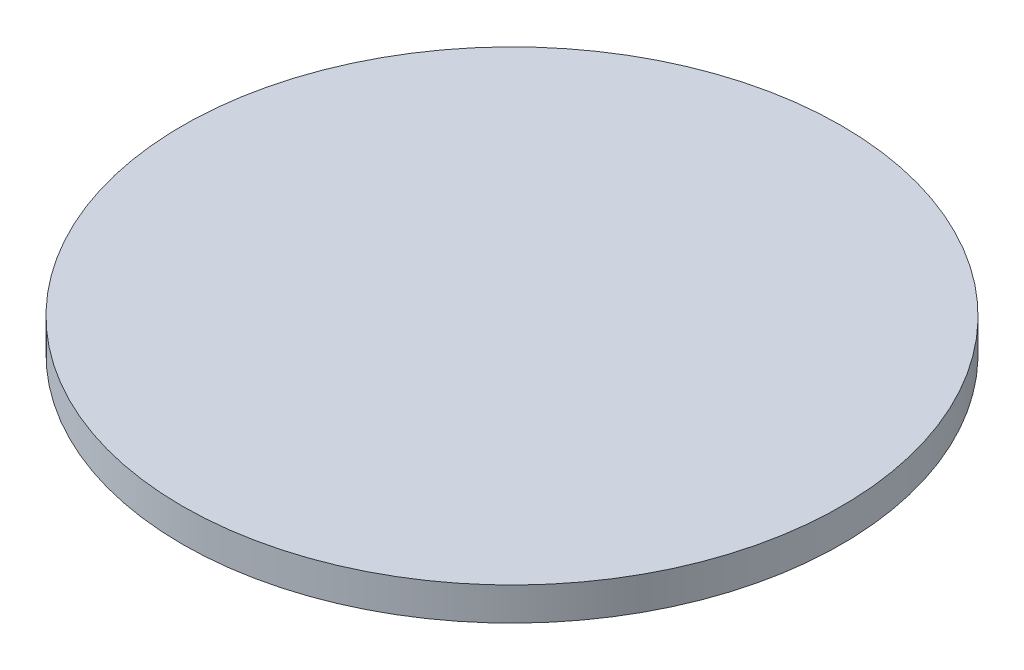
SolidWorks part; units mm, degrees
ref_plane "Front Plane" through (0, 0, 0) normal (0, 0, 1) x (1, 0, 0)
ref_plane "Top Plane" through (0, 0, 0) normal (0, 1, 0) x (1, 0, 0)
ref_plane "Right Plane" through (0, 0, 0) normal (1, 0, 0) x (0, 0, -1)
sketch "Sketch1" plane through (0, 0, 0) normal (0, 1, 0) x (1, 0, 0)
  circle A0 centre (0, 0) radius 31.75
  dimension "D1" = 63.5
extrude "Boss-Extrude1" add sketch "Sketch1" along normal blind 3.18
